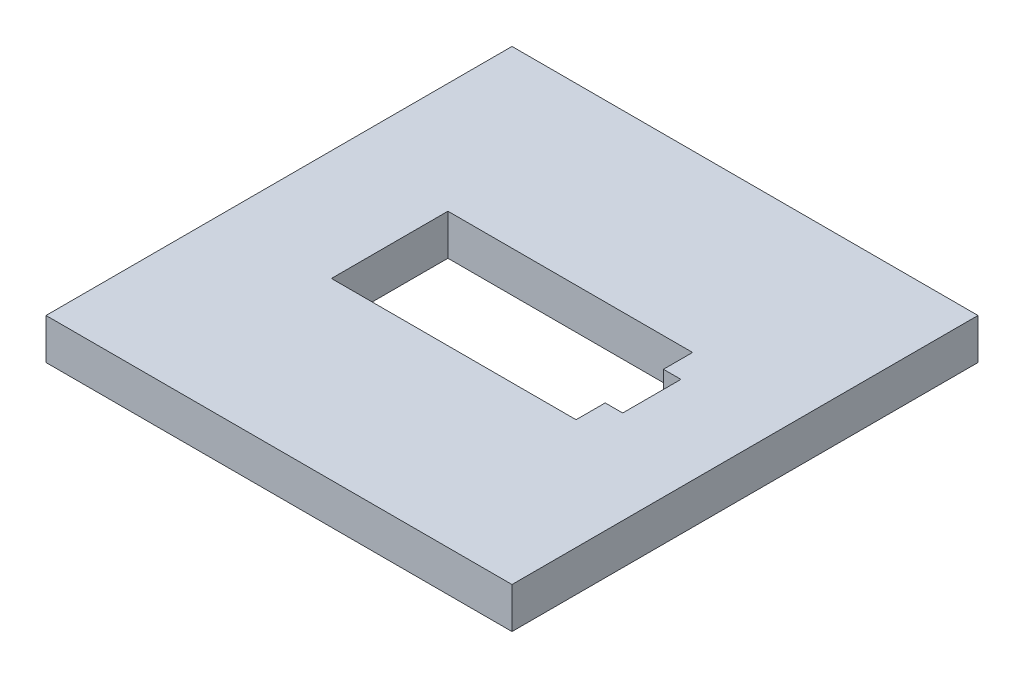
SolidWorks part; units mm, degrees
ref_plane "Alzado" through (0, 0, 0) normal (0, 0, 1) x (1, 0, 0)
ref_plane "Planta" through (0, 0, 0) normal (0, 1, 0) x (1, 0, 0)
ref_plane "Vista lateral" through (0, 0, 0) normal (1, 0, 0) x (0, 0, -1)
sketch "Croquis1" plane through (0, 0, 0) normal (0, 1, 0) x (1, 0, 0)
  line L1 (-40, -40) -> (40, -40)
  line L2 (-40, -40) -> (-40, 40)
  line L3 (-40, 40) -> (40, 40)
  line L4 (40, -40) -> (40, 40)
  line L5 (-40, -40) -> (40, 40) construction
  line L6 (-40, 40) -> (40, -40) construction
  circle A0 centre (0, 0) radius 35 construction
  point P0 (0, 0)
  dimension "D2" = 70
  dimension "D1" = 80
  dimension "D3" = 80
extrude "Saliente-Extruir1" add sketch "Croquis1" along normal blind 7
sketch "Croquis2" plane through (0, 7, 0) normal (0, 1, 0) x (1, 0, 0)
  line L0 (21, 5) -> (24, 5)
  line L1 (-21, -10) -> (21, -10)
  line L2 (-21, -10) -> (-21, 10)
  line L3 (-21, 10) -> (21, 10)
  line L4 (21, -10) -> (21, -5)
  line L5 (-21, -10) -> (21, 10) construction
  line L6 (-21, 10) -> (21, -10) construction
  line L7 (24, 5) -> (24, -5)
  line L8 (24, -5) -> (21, -5)
  line L9 (21, 5) -> (21, 10)
  point P0 (0, 0)
  point P10 (24, 0)
  dimension "D1" = 42
  dimension "D2" = 20
  dimension "D3" = 10
  dimension "D4" = 3
extrude "Cortar-Extruir1" cut sketch "Croquis2" against normal through all
equation "\"A\"= 80mm"
equation "\"D1@Croquis1\"=\"A\""
equation "\"D3@Croquis1\"=\"A\""
